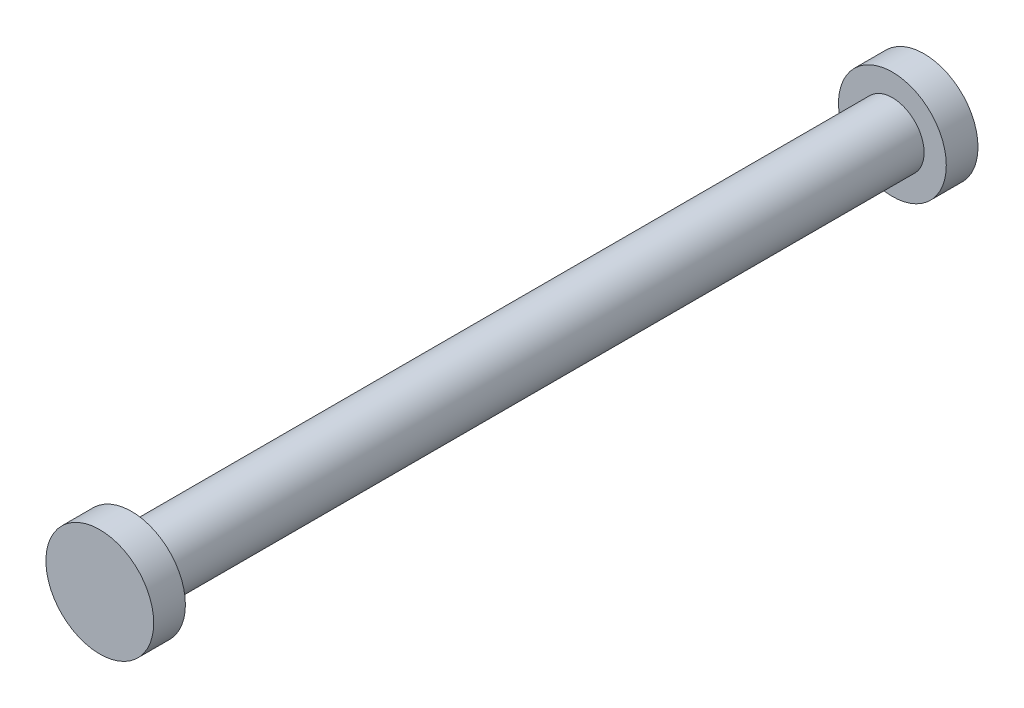
SolidWorks part; units mm, degrees
ref_plane "Alzado" through (0, 0, 0) normal (0, 0, 1) x (1, 0, 0)
ref_plane "Planta" through (0, 0, 0) normal (0, 1, 0) x (1, 0, 0)
ref_plane "Vista lateral" through (0, 0, 0) normal (1, 0, 0) x (0, 0, -1)
sketch3d "Sk_Eje"
  line L0 (-425.1, 65, -65) -> (-425.1, 65, 65)
sweep "Eje" add path "Sk_Eje" circular profile diameter 10 parameters "D3"=10
sketch3d "Sk_Tuerca_dcha"
  line L0 (-425.1, 65, 60) -> (-425.1, 65, 65)
sweep "Tuerca_dcha" add path "Sk_Tuerca_dcha" circular profile diameter 17 parameters "D3"=17
sketch3d "Sk_Tuerca_izq"
  line L0 (-425.1, 65, -65) -> (-425.1, 65, -60)
sweep "Tuerca_izq" add path "Sk_Tuerca_izq" circular profile diameter 17 parameters "D3"=17
